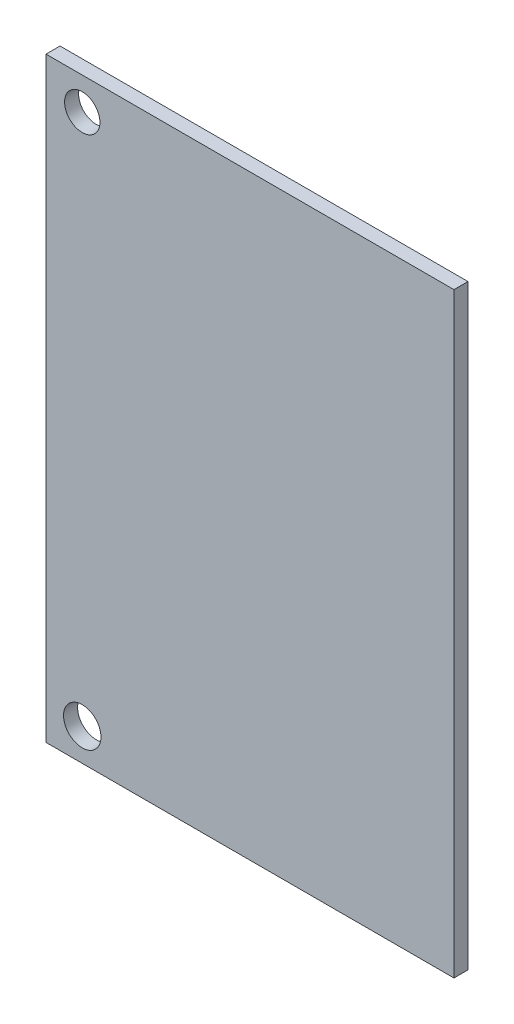
SolidWorks part; units mm, degrees
ref_plane "Спереди" through (0, 0, 0) normal (0, 0, 1) x (1, 0, 0)
ref_plane "Сверху" through (0, 0, 0) normal (0, 1, 0) x (1, 0, 0)
ref_plane "Справа" through (0, 0, 0) normal (1, 0, 0) x (0, 0, -1)
sketch "Эскиз1" plane through (0, 0, 0) normal (0, 0, 1) x (1, 0, 0)
  line L0 (-336.9233, 30.5326) -> (-273.3233, -14.9674) construction
  line L1 (-340.0233, 33.2826) -> (-270.2233, 33.2826)
  line L2 (-340.0233, 33.2826) -> (-340.0233, -17.7174)
  line L3 (-340.0233, -17.7174) -> (-270.2233, -17.7174)
  line L4 (-270.2233, 33.2826) -> (-270.2233, -17.7174)
  line L5 (-273.3233, 30.5326) -> (-336.9233, -14.9674) construction
  circle A0 centre (-336.9233, 30.5326) radius 1.5121
  circle A1 centre (-336.9233, -14.9674) radius 1.6
  circle A2 centre (-273.3233, 30.5326) radius 1.6
  circle A3 centre (-273.3233, -14.9674) radius 1.6
  point P6 (-305.1233, 33.2826)
  point P9 (-305.1233, 7.7826)
  point P12 (-270.2233, 7.7826)
  dimension "D3" = 63.6
  dimension "D1" = 51
  dimension "D2" = 69.8
  dimension "D4" = 45.5
extrude "Бобышка-Вытянуть1" add sketch "Эскиз1" along normal blind 1.2
sketch "Эскиз2" plane through (0, 0, 1.2) normal (0, 0, 1) x (1, 0, 0)
  line L0 (-270.2233, 33.2826) -> (-340.0233, 33.2826) construction
  line L1 (-305.1233, 33.2826) -> (-270.2233, 33.2826)
  line L2 (-305.1233, 33.2826) -> (-305.1233, -17.7174)
  line L3 (-305.1233, -17.7174) -> (-270.2233, -17.7174)
  line L4 (-270.2233, 33.2826) -> (-270.2233, -17.7174)
extrude "Вырез-Вытянуть1" cut sketch "Эскиз2" against normal through all
